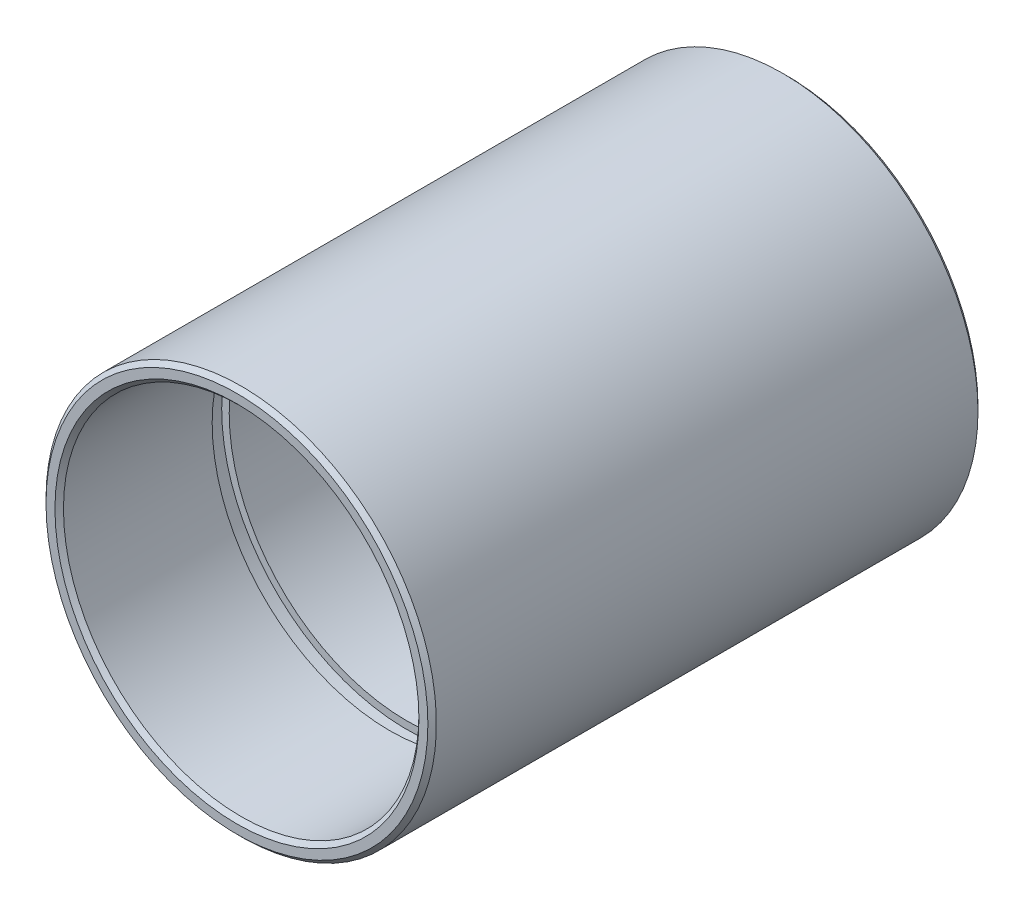
SolidWorks part; units mm, degrees
material "Tungsten"
ref_plane "Front" through (0, 0, 0) normal (0, 0, 1) x (1, 0, 0)
ref_plane "Top" through (0, 0, 0) normal (0, 1, 0) x (1, 0, 0)
ref_plane "Right" through (0, 0, 0) normal (1, 0, 0) x (0, 0, -1)
sketch "Sketch1" plane through (0, 0, 0) normal (0, 0, 1) x (1, 0, 0)
  circle A0 centre (0, 0) radius 17.4625
  circle A1 centre (0, 0) radius 15.9004
  dimension "D1" = 31.8008
  dimension "D2" = 34.925
extrude "Base-Extrude" add sketch "Sketch1" along normal blind 49.2125
ref_plane "Plane4" through (0, 0, 15.2082) normal (0, 0, 1) x (1, 0, 0)
sketch "Sketch2" plane through (0, 0, 15.2082) normal (0, 0, 1) x (1, 0, 0)
  circle A0 centre (0, 0) radius 16.5735
  dimension "D1" = 33.147
extrude "Cut-Extrude1" cut sketch "Sketch2" against normal blind 1.524
ref_plane "Plane5" through (0, 0, 34.0042) normal (0, 0, 1) x (1, 0, 0)
sketch "Sketch3" plane through (0, 0, 34.0042) normal (0, 0, 1) x (1, 0, 0)
  circle A0 centre (0, 0) radius 16.5735
  dimension "D1" = 33.147
extrude "Cut-Extrude2" cut sketch "Sketch3" along normal blind 1.524
chamfer "Chamfer1" distance 0.381 angle 45 4 edges at (17.4625, 0, 0) (17.4625, 0, 49.2125) (15.9004, 0, 0) (15.9004, 0, 49.2125)
